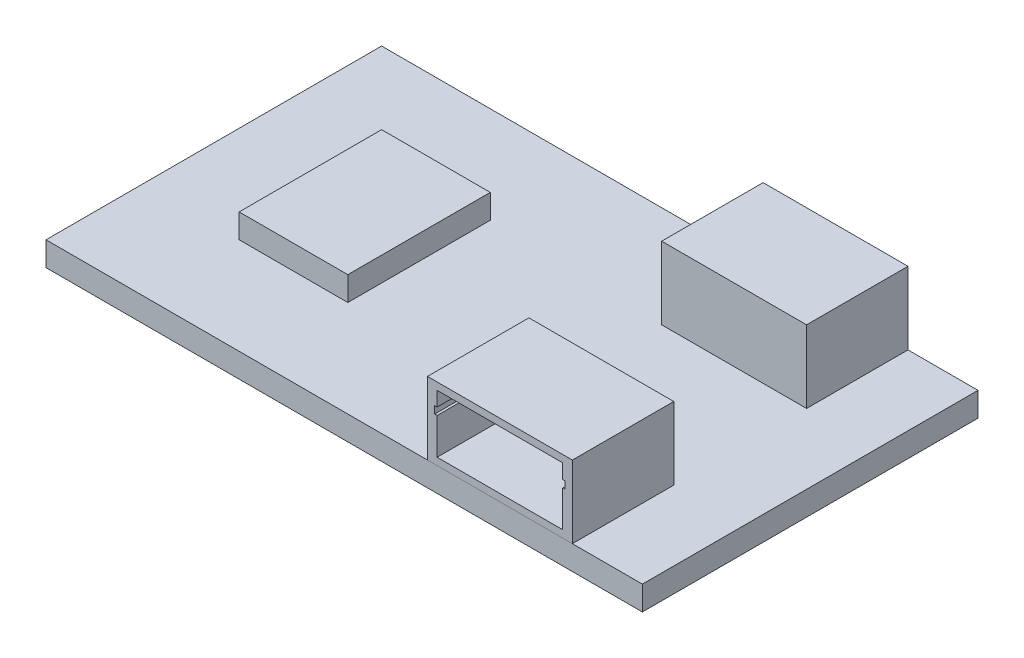
SolidWorks part; units mm, degrees
ref_plane "Front" through (0, 0, 0) normal (0, 0, 1) x (1, 0, 0)
ref_plane "Top" through (0, 0, 0) normal (0, 1, 0) x (1, 0, 0)
ref_plane "Right" through (0, 0, 0) normal (1, 0, 0) x (0, 0, -1)
sketch "Sketch1" plane through (0, 0, 0) normal (0, 1, 0) x (1, 0, 0)
  line L1 (-12.35, 6.95) -> (12.35, 6.95)
  line L2 (-12.35, 6.95) -> (-12.35, -6.95)
  line L3 (-12.35, -6.95) -> (12.35, -6.95)
  line L4 (12.35, 6.95) -> (12.35, -6.95)
  line L5 (-12.35, 6.95) -> (12.35, -6.95) construction
  line L6 (-12.35, -6.95) -> (12.35, 6.95) construction
  point P0 (0, 0)
  dimension "D1" = 24.7
  dimension "D2" = 13.9
extrude "Boss-Extrude1" add sketch "Sketch1" along normal blind 1
sketch "Sketch2" plane through (0, 1, 0) normal (0, 1, 0) x (1, 0, 0)
  line L0 (9.45, -6.95) -> (3.45, -6.95)
  line L1 (9.45, -6.95) -> (9.45, -2.75)
  line L2 (3.45, -6.95) -> (3.45, -2.75)
  line L3 (9.45, -2.75) -> (3.45, -2.75)
  line L4 (-12.35, -6.95) -> (12.35, -6.95) construction
  line L5 (12.35, -6.95) -> (12.35, 6.95) construction
  line L6 (-12.35, 0) -> (12.35, 0) construction
  line L7 (-12.35, 6.95) -> (-12.35, -6.95) construction
  line L8 (9.45, 6.95) -> (9.45, 2.75)
  line L9 (9.45, 6.95) -> (3.45, 6.95)
  line L10 (3.45, 6.95) -> (3.45, 2.75)
  line L11 (9.45, 2.75) -> (3.45, 2.75)
  dimension "D1" = 2.9
  dimension "D2" = 4.2
  dimension "D3" = 6
extrude "Boss-Extrude2" add sketch "Sketch2" along normal blind 3 separate body
sketch "Sketch3" plane through (0, 0, 6.95) normal (0, 0, 1) x (1, 0, 0)
  line L0 (3.85, 3.7) -> (3.85, 3.1)
  line L1 (3.85, 3.1) -> (3.75, 3.1)
  line L2 (3.75, 3.1) -> (3.75, 2.8)
  line L3 (3.75, 2.8) -> (3.85, 2.8)
  line L4 (3.85, 2.8) -> (3.85, 1.3)
  line L5 (6.45, 4) -> (6.45, 0) construction
  line L6 (3.45, 4) -> (9.45, 4) construction
  line L7 (-12.35, 0) -> (12.35, 0) construction
  line L8 (3.85, 1.3) -> (9.05, 1.3)
  line L10 (9.05, 3.7) -> (3.85, 3.7)
  line L11 (3.45, 4) -> (3.45, 1) construction
  line L12 (-12.35, 1) -> (12.35, 1) construction
  line L13 (9.05, 2.8) -> (9.05, 1.3)
  line L14 (9.15, 2.8) -> (9.05, 2.8)
  line L15 (9.15, 3.1) -> (9.15, 2.8)
  line L16 (9.05, 3.1) -> (9.15, 3.1)
  line L17 (9.05, 3.7) -> (9.05, 3.1)
  dimension "D1" = 0.3
  dimension "D2" = 0.3
  dimension "D3" = 0.1
  dimension "D4" = 0.1
  dimension "D5" = 0.3
  dimension "D6" = 0.6
  dimension "D7" = 0.3
sketch "Sketch4" plane through (0, 1, 0) normal (0, 1, 0) x (1, 0, 0)
  line L0 (-12.35, 0) -> (12.35, 0) construction
  line L1 (-12.35, 6.95) -> (-12.35, -6.95) construction
  line L2 (12.35, -6.95) -> (12.35, 6.95) construction
extrude "Cut-Extrude1" cut sketch "Sketch3" against normal blind 3
sketch "Sketch5" plane through (0, 0, -6.95) normal (0, 0, -1) x (-1, 0, 0)
  line L0 (-9.15, 3.7) -> (-9.15, 3.1)
  line L1 (-9.15, 3.1) -> (-9.25, 3.1)
  line L2 (-9.25, 3.1) -> (-9.25, 2.8)
  line L3 (-9.25, 2.8) -> (-9.15, 2.8)
  line L4 (-9.15, 2.8) -> (-9.15, 1.3)
  line L5 (-6.5592, -5.0038) -> (-6.5592, -1.7799) construction
  line L14 (-9.45, 4) -> (-9.45, 1) construction
  line L15 (-6.45, 4) -> (-6.45, 1) construction
  line L18 (-9.45, 4) -> (-3.45, 4) construction
  line L19 (12.35, 1) -> (-12.35, 1) construction
  line L20 (-9.15, 3.7) -> (-3.75, 3.7)
  line L22 (-3.75, 1.3) -> (-9.15, 1.3)
  line L23 (-3.75, 3.7) -> (-3.75, 3.1)
  line L24 (-3.75, 3.1) -> (-3.65, 3.1)
  line L25 (-3.65, 3.1) -> (-3.65, 2.8)
  line L26 (-3.65, 2.8) -> (-3.75, 2.8)
  line L27 (-3.75, 2.8) -> (-3.75, 1.3)
  point P21 (-9.25, 2.95)
  dimension "D1" = 0.3
  dimension "D2" = 0.3
  dimension "D3" = 0.3
  dimension "D4" = 0.1
  dimension "D5" = 0.3
  dimension "D6" = 0.3
extrude "Cut-Extrude2" cut sketch "Sketch5" against normal blind 3
sketch "Sketch6" plane through (0, 1, 0) normal (0, 1, 0) x (1, 0, 0)
  line L0 (-12.35, 6.95) -> (-12.35, -6.95) construction
  line L1 (-8.35, 2.95) -> (-3.85, 2.95)
  line L2 (-8.35, 2.95) -> (-8.35, -2.95)
  line L3 (-8.35, -2.95) -> (-3.85, -2.95)
  line L4 (-3.85, 2.95) -> (-3.85, -2.95)
  line L5 (-8.35, 2.95) -> (-3.85, -2.95) construction
  line L6 (-8.35, -2.95) -> (-3.85, 2.95) construction
  line L7 (12.35, 6.95) -> (-12.35, 6.95) construction
  line L8 (-12.35, -6.95) -> (12.35, -6.95) construction
  point P0 (-6.1, 0)
  point P9 (-6.1, 2.95)
  dimension "D1" = 4
  dimension "D2" = 4
  dimension "D3" = 4
  dimension "D4" = 4.5
extrude "Boss-Extrude3" add sketch "Sketch6" along normal blind 1
